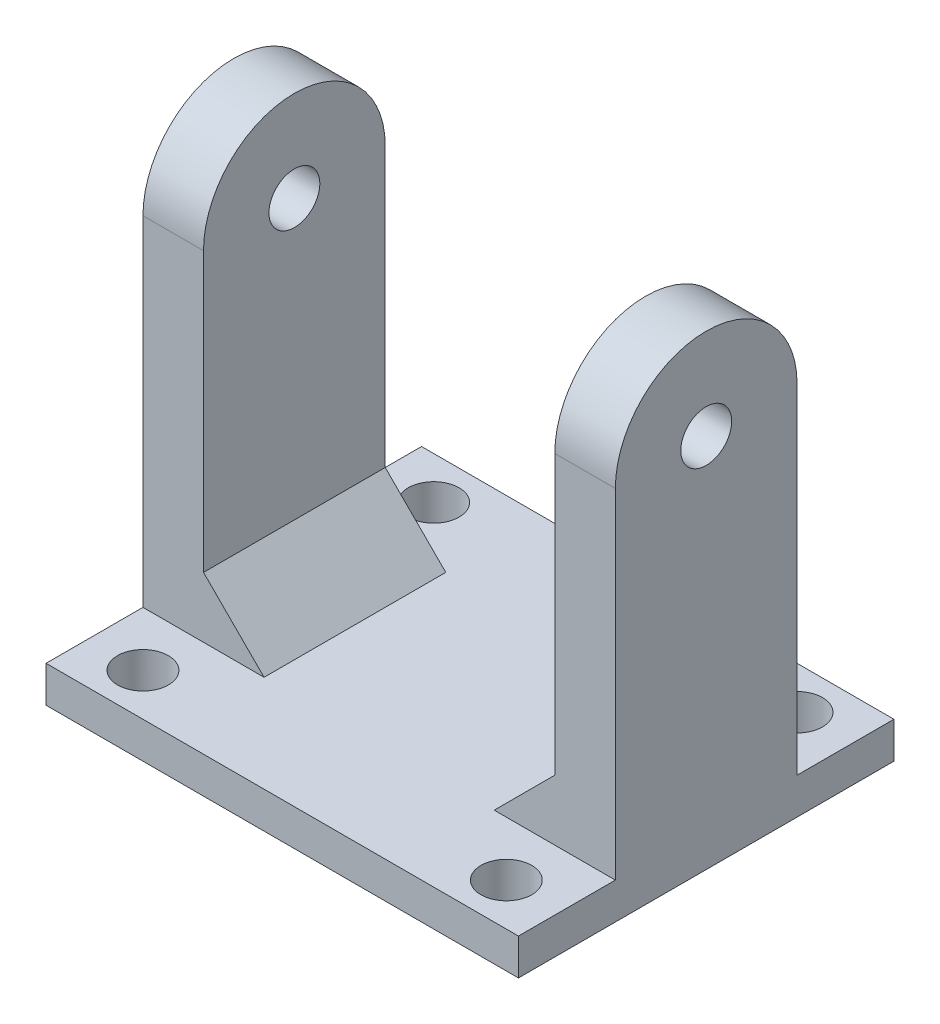
SolidWorks part; units mm, degrees
ref_plane "前视基准面" through (0, 0, 0) normal (0, 0, 1) x (1, 0, 0)
ref_plane "上视基准面" through (0, 0, 0) normal (0, 1, 0) x (1, 0, 0)
ref_plane "右视基准面" through (0, 0, 0) normal (1, 0, 0) x (0, 0, -1)
other "Configuration Table"
sketch "草图1" plane through (0, 0, 0) normal (0, 1, 0) x (1, 0, 0)
  line L0 (-19.5, 15.5) -> (19.5, 15.5)
  line L1 (19.5, 15.5) -> (19.5, -15.5)
  line L2 (-19.5, 15.5) -> (-19.5, -15.5)
  line L3 (-19.5, -15.5) -> (19.5, -15.5)
  dimension "D1" = 39
  dimension "D2" = 31
  dimension "D3" = 19.5
  dimension "D4" = 15.5
extrude "凸台-拉伸1" add sketch "草图1" along normal blind 3
sketch "草图5" plane through (-19.5, 0, 0) normal (-1, 0, 0) x (0, 0, 1)
  line L0 (0, 5.1574) -> (0, 32.5419) construction
  line L1 (-10.7124, 31) -> (15.3123, 31) construction
  line L2 (-7.5, 31) -> (-7.5, 3)
  line L3 (-15.5, 3) -> (15.5, 3) construction
  line L4 (7.5, 31) -> (7.5, 3)
  arc A0 (7.5, 31) -> (-7.5, 31) centre (0, 31) ccw
  circle A1 centre (0, 31) radius 2.1
  line M7 (15.5, 3) -> (-15.5, 3)
  dimension "D1" = 15
  dimension "D3" = 4.2
  dimension "D2" = 28
extrude "凸台-拉伸2" add sketch "草图5" against normal blind 5 contours L4 A0 L2 A1 M7
sketch "草图6" plane through (19.5, 0, 0) normal (1, 0, 0) x (0, 0, -1)
  line L3 (-7.5, 31) -> (-7.5, 3)
  line L4 (-7.5, 3) -> (7.5, 3)
  line L5 (7.5, 3) -> (7.5, 31)
  line L6 (-7.5, 31) -> (-7.5, 3)
  line L8 (7.5, 3) -> (7.5, 31)
  line L11 (-7.5, 3) -> (7.5, 3)
  circle A0 centre (0, 31) radius 2.1
  arc A1 (7.5, 31) -> (-7.5, 31) centre (0, 31) ccw
  arc A2 (7.5, 31) -> (-7.5, 31) centre (0, 31) ccw
  dimension "D2" = 4.2
  dimension "D1" = 0
extrude "凸台-拉伸3" add sketch "草图6" against normal blind 5
sketch "草图8" plane through (0, 0, 0) normal (0, -1, 0) x (1, 0, 0)
  line L0 (-23.8748, 0) -> (23.696, 0) construction
  line L1 (0, 17.2131) -> (0, -17.6602) construction
  circle A0 centre (-15, 12) radius 2.1
  circle A1 centre (-15, -12) radius 2.1
  circle A2 centre (15, -12) radius 2.1
  circle A3 centre (15, 12) radius 2.1
  dimension "D1" = 4.2
  dimension "D2" = 4.2
  dimension "D3" = 12
  dimension "D4" = 12
  dimension "D5" = 15
  dimension "D6" = 15
extrude "切除-拉伸1" cut sketch "草图8" against normal through all contours A3 | A2 | A0 | A1
chamfer "倒角1" distance 5 angle 45 2 edges at (14.5, 3, 0) (-14.5, 3, 0)
